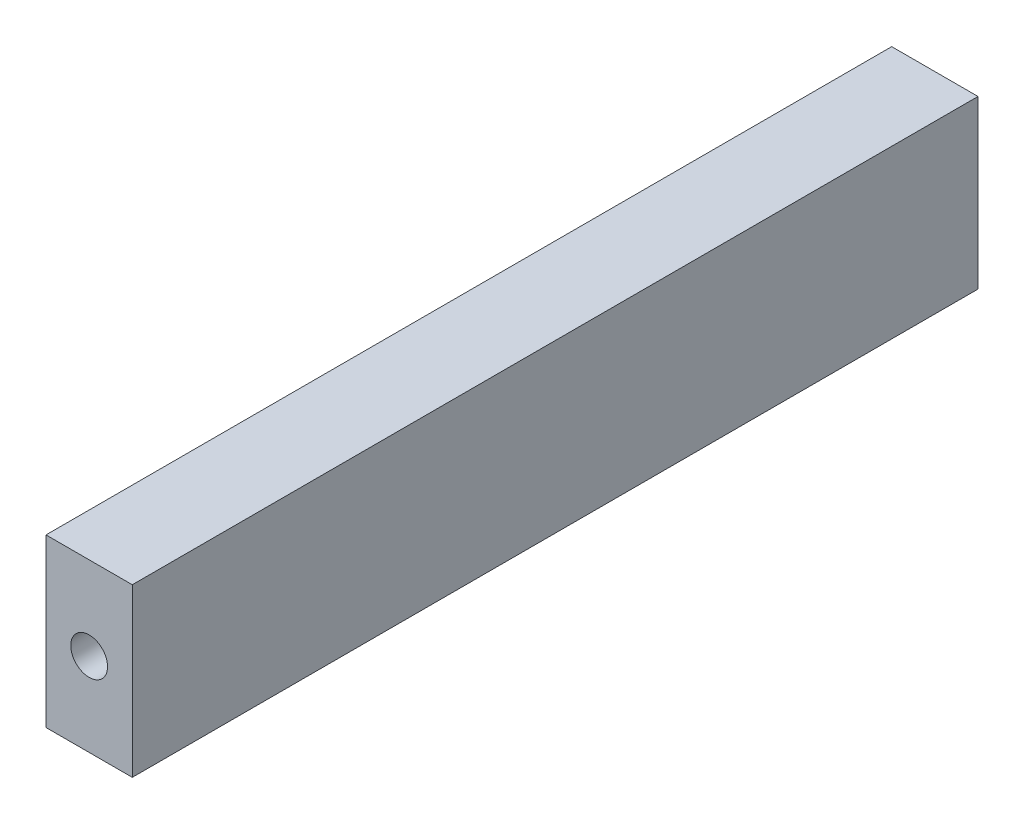
SolidWorks part; units mm, degrees
ref_plane "Front Plane" through (0, 0, 0) normal (0, 0, 1) x (1, 0, 0)
ref_plane "Top Plane" through (0, 0, 0) normal (0, 1, 0) x (1, 0, 0)
ref_plane "Right Plane" through (0, 0, 0) normal (1, 0, 0) x (0, 0, -1)
sketch "Sketch1" plane through (0, 0, 0) normal (0, 0, 1) x (1, 0, 0)
  line L1 (-41.9849, 34.6734) -> (-26.9849, 34.6734)
  line L2 (-41.9849, 34.6734) -> (-41.9849, 5.6734)
  line L3 (-41.9849, 5.6734) -> (-26.9849, 5.6734)
  line L4 (-26.9849, 34.6734) -> (-26.9849, 5.6734)
  line L5 (-41.9849, 34.6734) -> (-26.9849, 5.6734) construction
  line L6 (-41.9849, 5.6734) -> (-26.9849, 34.6734) construction
  point P0 (-34.4849, 20.1734)
  dimension "D1" = 15
  dimension "D2" = 29
extrude "Boss-Extrude1" add sketch "Sketch1" along normal blind 147
sketch "Sketch2" plane through (0, 0, 147) normal (0, 0, 1) x (1, 0, 0)
  line L0 (-41.9849, 34.6734) -> (-26.9849, 5.6734) construction
  line L1 (-41.9849, 5.6734) -> (-26.9849, 34.6734) construction
  circle A0 centre (-34.4849, 20.1734) radius 3.2
  dimension "D1" = 6.4
extrude "Cut-Extrude1" cut sketch "Sketch2" against normal blind 9.5
ref_plane "Plane1" through (0, 0, 73.5) normal (0, 0, 1) x (1, 0, 0)
mirror "Mirror1" about plane through (0, 0, 73.5) normal (0, 0, 1) of "Cut-Extrude1"
